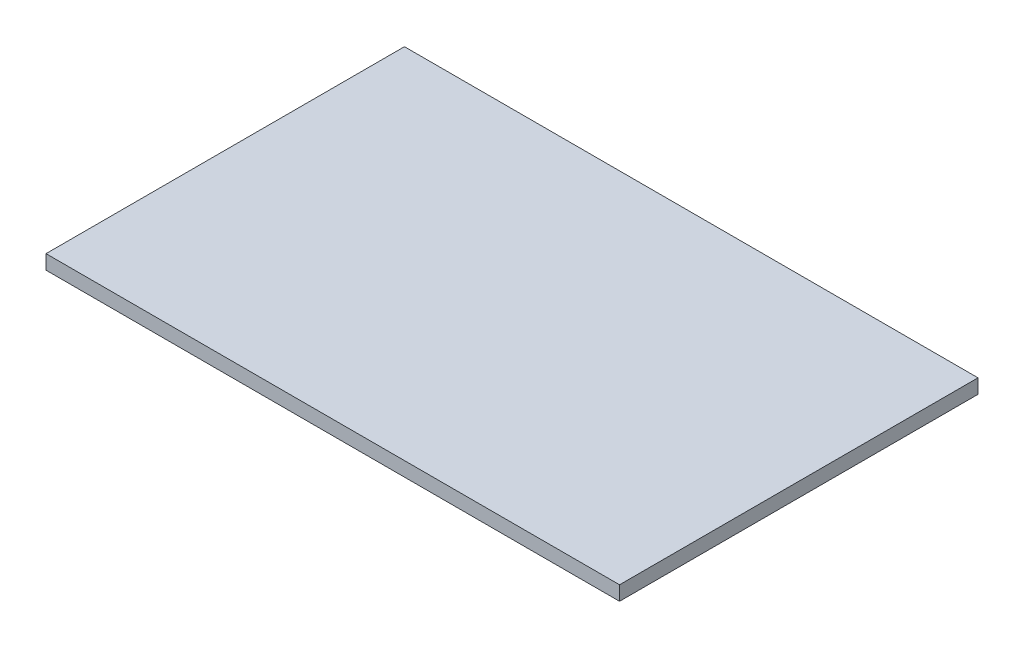
SolidWorks part; units mm, degrees
ref_plane "Front Plane" through (0, 0, 0) normal (0, 0, 1) x (1, 0, 0)
ref_plane "Top Plane" through (0, 0, 0) normal (0, 1, 0) x (1, 0, 0)
ref_plane "Right Plane" through (0, 0, 0) normal (1, 0, 0) x (0, 0, -1)
sketch "Sketch1" plane through (0, 0, 0) normal (0, 1, 0) x (1, 0, 0)
  line L1 (-22.8255, 19.8892) -> (17.1745, 19.8892)
  line L2 (-22.8255, 19.8892) -> (-22.8255, -5.1108)
  line L3 (-22.8255, -5.1108) -> (17.1745, -5.1108)
  line L4 (17.1745, 19.8892) -> (17.1745, -5.1108)
  dimension "D1" = 40
  dimension "D2" = 25
extrude "Boss-Extrude1" add sketch "Sketch1" along normal blind 1
